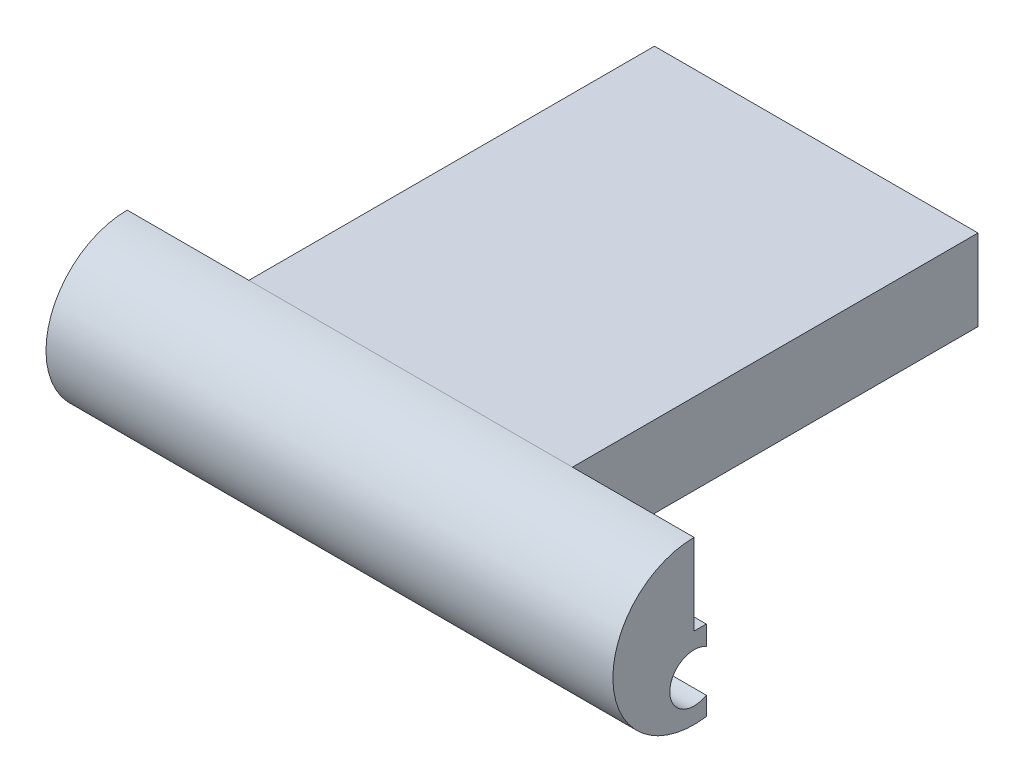
SolidWorks part; units mm, degrees
material "Ductile Iron"
ref_plane "Front Plane" through (0, 0, 0) normal (0, 0, 1) x (1, 0, 0)
ref_plane "Top Plane" through (0, 0, 0) normal (0, 1, 0) x (1, 0, 0)
ref_plane "Right Plane" through (0, 0, 0) normal (1, 0, 0) x (0, 0, -1)
sketch "Sketch1" plane through (0, 0, 0) normal (0, 0, 1) x (1, 0, 0)
  line L1 (174.9804, 176.5819) -> (-223.8996, 176.5819)
  line L2 (174.9804, 176.5819) -> (174.9804, 276.5819)
  line L3 (174.9804, 276.5819) -> (-223.8996, 276.5819)
  line L4 (-223.8996, 176.5819) -> (-223.8996, 276.5819)
  line L5 (174.9804, 176.5819) -> (-223.8996, 276.5819) construction
  line L6 (174.9804, 276.5819) -> (-223.8996, 176.5819) construction
  point P0 (-24.4596, 226.5819)
  dimension "D1" = 398.88
  dimension "D2" = 100
extrude "Boss-Extrude1" add sketch "Sketch1" along normal blind 500
ref_plane "Plane1" through (-373.8996, 0, 0) normal (-1, 0, 0) x (0, 0, 1)
sketch "Sketch2" plane through (-373.8996, 0, 0) normal (-1, 0, 0) x (0, 0, 1)
  line L0 (500, 276.5819) -> (500, 176.5819)
  line L1 (500, 176.5819) -> (485, 176.5819)
  line L2 (500, 176.5819) -> (0, 176.5819) construction
  line L3 (485, 176.5819) -> (485, 152.5819)
  line L4 (485, 77.7319) -> (485, 100.6219)
  arc A0 (485, 100.6219) -> (485, 152.5819) centre (500.0013, 126.6019) ccw
  arc A1 (485, 77.7319) -> (500, 276.5819) centre (500.1216, 176.582) ccw
  dimension "D5" = 60
  dimension "D6" = 200
  dimension "D1" = 15
  dimension "D2" = 24
  dimension "D3" = 51.96
  dimension "D4" = 22.89
extrude "Boss-Extrude2" add sketch "Sketch2" against normal blind 698.88
